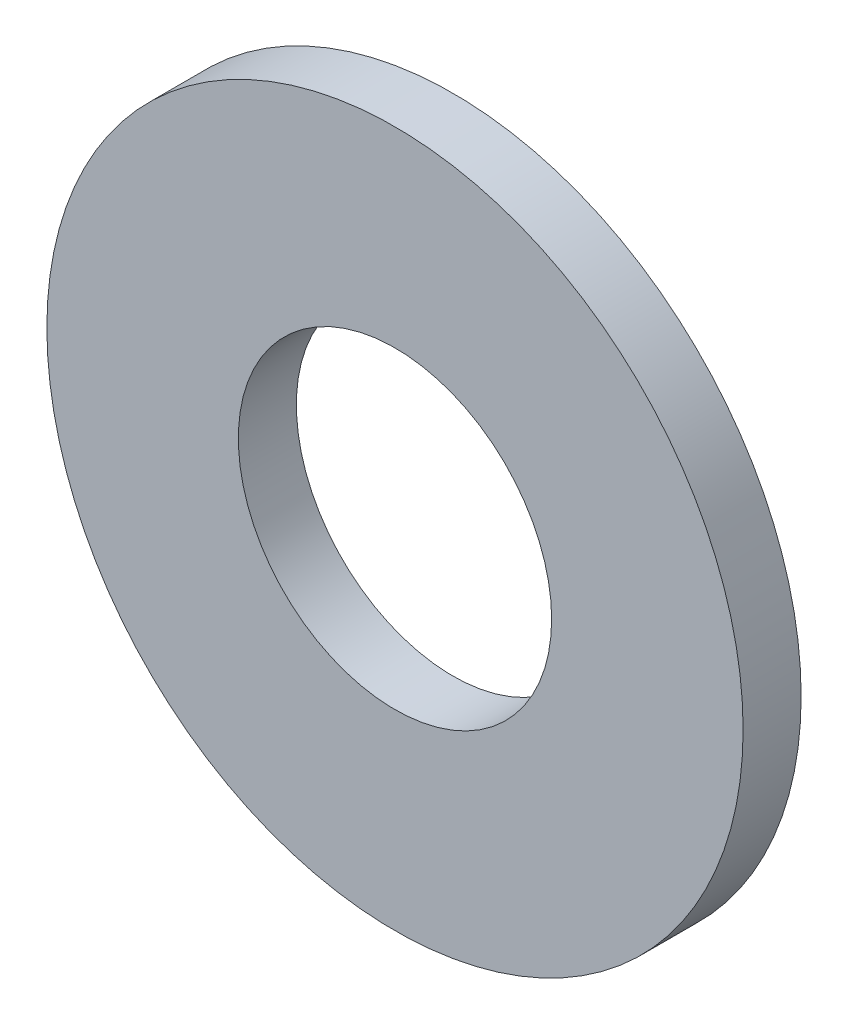
SolidWorks part; units mm, degrees
ref_plane "Front" through (0, 0, 0) normal (0, 0, 1) x (1, 0, 0)
ref_plane "Top" through (0, 0, 0) normal (0, 1, 0) x (1, 0, 0)
ref_plane "Right" through (0, 0, 0) normal (1, 0, 0) x (0, 0, -1)
sketch "Sketch1" plane through (0, 0, 0) normal (0, 0, 1) x (1, 0, 0)
  circle A0 centre (0, 0) radius 1.35
  circle A1 centre (0, 0) radius 3
  dimension "d1" = 2.7
  dimension "d2" = 6
extrude "Base-Extrude" add sketch "Sketch1" against normal blind 0.5
